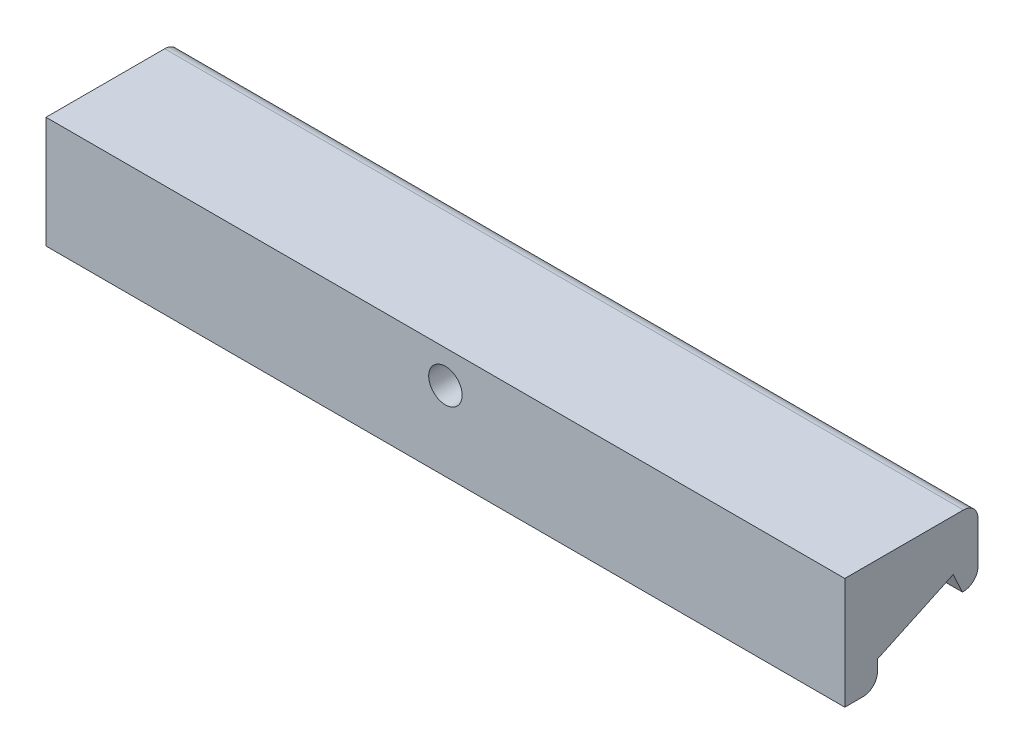
SolidWorks part; units mm, degrees
ref_plane "Front Plane" through (0, 0, 0) normal (0, 0, 1) x (1, 0, 0)
ref_plane "Top Plane" through (0, 0, 0) normal (0, 1, 0) x (1, 0, 0)
ref_plane "Right Plane" through (0, 0, 0) normal (1, 0, 0) x (0, 0, -1)
sketch "Sketch1" plane through (0, 0, 0) normal (1, 0, 0) x (0, 0, -1)
  line L0 (0, 0) -> (2.4995, 0)
  line L2 (18.3407, 7.6355) -> (18.3407, 13.3601)
  line L3 (16.3407, 15.3601) -> (0, 15.3601)
  line L4 (0, 15.3601) -> (0, 0)
  line L6 (16.1904, 5.6412) -> (14.9225, 8.3601)
  line L7 (14.9225, 8.3601) -> (4.5, 3.5)
  line L8 (4.5, 3.5) -> (4.5, 2.0005)
  arc A0 (16.3407, 15.3601) -> (18.3407, 13.3601) centre (16.3407, 13.3601) cw
  arc A1 (16.1904, 5.6412) -> (18.3407, 7.6355) centre (16.3407, 7.6355) ccw
  arc A2 (2.4995, 0) -> (4.5, 2.0005) centre (2.4995, 2.0005) ccw
  dimension "D7" = 4
  dimension "D4" = 4
  dimension "D8" = 4.0011
  dimension "D3" = 11.5
  dimension "D1" = 4.5
  dimension "D5" = 7
  dimension "D6" = 3
extrude "ProfileBoss-Extrude1" add sketch "Sketch1" along normal blind 110
sketch "Sketch3" plane through (0, 0, 0) normal (0, 0, 1) x (1, 0, 0)
  line L0 (0, 15.3601) -> (0, 0) construction
  circle A0 centre (55, 10.8601) radius 2.3
  dimension "D1" = 4.6
  dimension "D4" = 4.5
  dimension "D2" = 55
extrude "MountingHolesCut-Extrude3" cut sketch "Sketch3" against normal blind 4.5
equation "\"LightStripShortLength\"= 80mm"
equation "\"D1@ProfileBoss-Extrude1\" = \"LightStripMidLength\""
equation "\"LightStripWidth\"= 11.5mm'Spec"
equation "\"D3@Sketch1\"=\"LightStripWidth\""
equation "\"LightStripGuideMountingHoleFromMiddle\"= \"LightStripMidLength\" / 2"
equation "\"D2@Sketch3\"=\"LightStripGuideMountingHoleFromMiddle\""
equation "\"LedStripLength\"= 270mm'Spec"
equation "\"LightStripMidLength\"= \"LedStripLength\" - \"LightStripShortLength\" * 2"
equation "\"LightStripGuideMountingHoleFromTop\"= 4.5mm"
equation "\"D4@Sketch3\"=\"LightStripGuideMountingHoleFromTop\""
